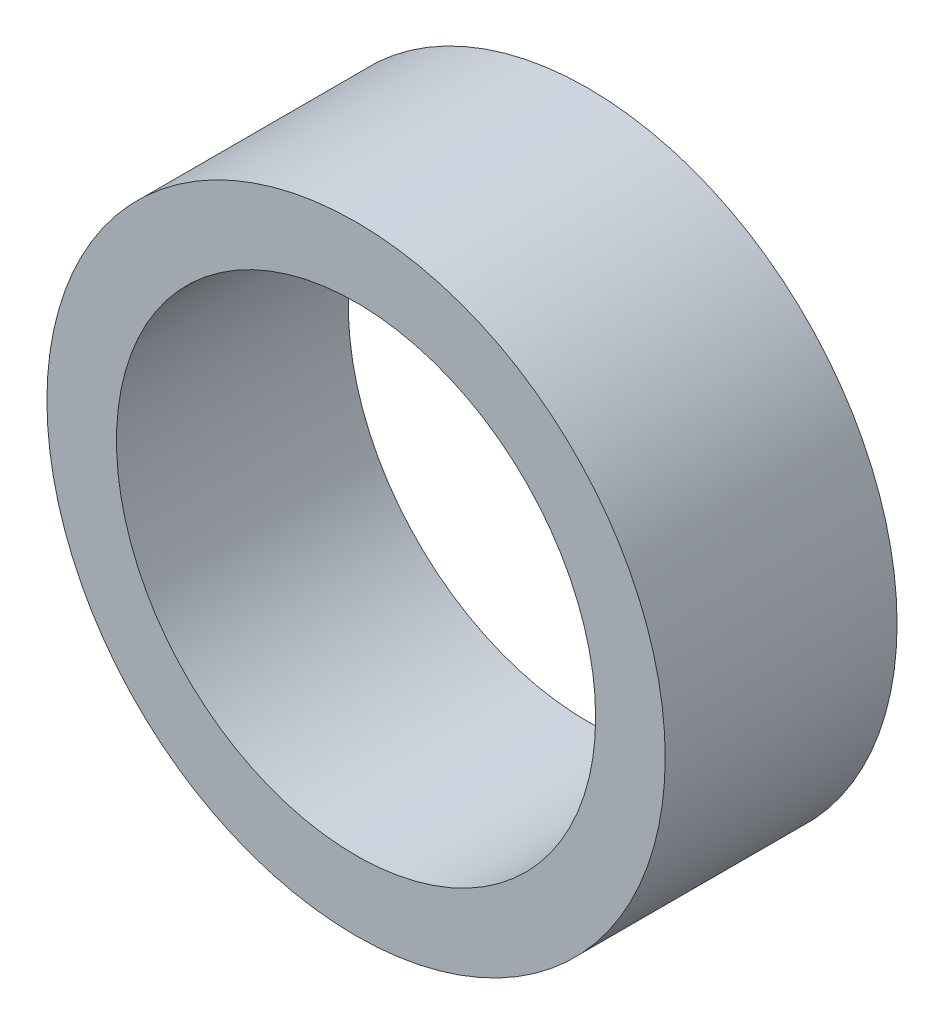
SolidWorks part; units mm, degrees
ref_plane "Front Plane" through (0, 0, 0) normal (0, 0, 1) x (1, 0, 0)
ref_plane "Top Plane" through (0, 0, 0) normal (0, 1, 0) x (1, 0, 0)
ref_plane "Right Plane" through (0, 0, 0) normal (1, 0, 0) x (0, 0, -1)
sketch "Sketch1" plane through (0, 0, 0) normal (0, 0, 1) x (1, 0, 0)
  circle A0 centre (0, 0) radius 3.1
  circle A1 centre (0, 0) radius 4
  dimension "D1" = 6.2
  dimension "D2" = 8
extrude "Boss-Extrude1" add sketch "Sketch1" along normal blind 3
equation "\"iw\"= 6.2mm'o"
equation "\"ow\"= 8mm"
equation "\"h\" = 3mm"
equation "\"D1@Sketch1\"=\"iw\""
equation "\"D2@Sketch1\"=\"ow\""
equation "\"D1@Boss-Extrude1\"=\"h\""
